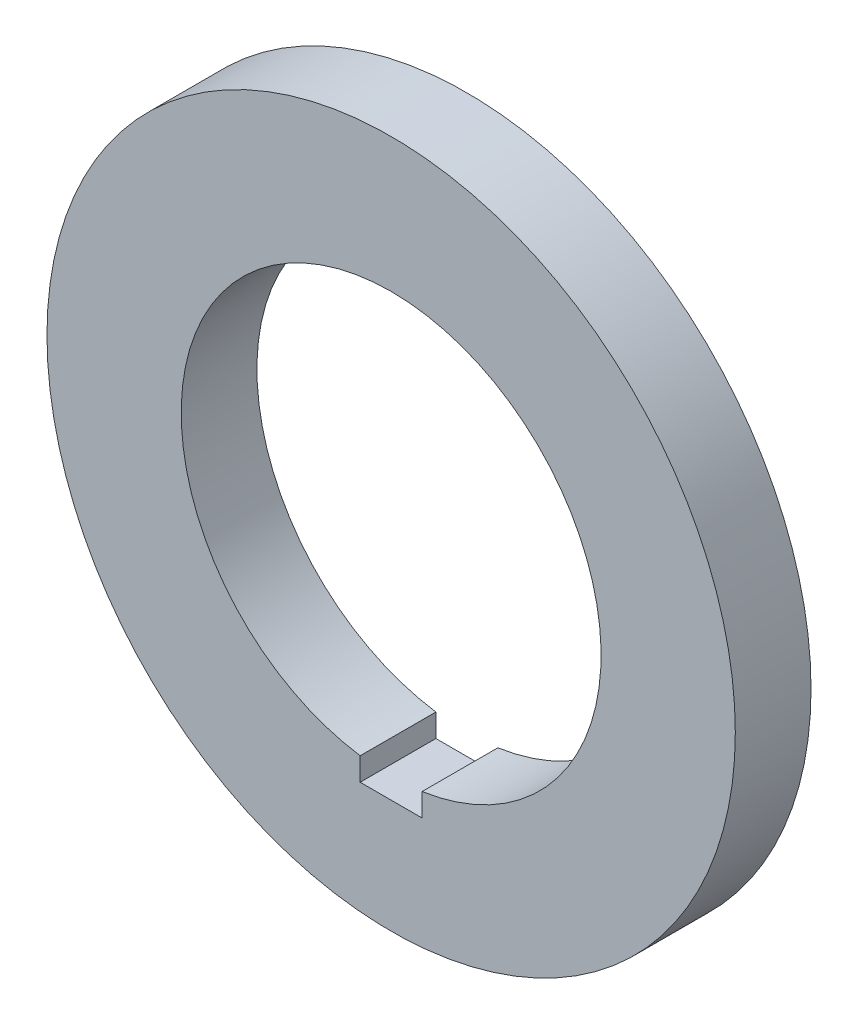
SolidWorks part; units mm, degrees
ref_plane "Front Plane" through (0, 0, 0) normal (0, 0, 1) x (1, 0, 0)
ref_plane "Top Plane" through (0, 0, 0) normal (0, 1, 0) x (1, 0, 0)
ref_plane "Right Plane" through (0, 0, 0) normal (1, 0, 0) x (0, 0, -1)
sketch "Sketch1" plane through (0, 0, 0) normal (0, 0, 1) x (1, 0, 0)
  circle A0 centre (0, 0) radius 25
  circle A1 centre (0, 0) radius 15.25
  dimension "D1" = 50
  dimension "D2" = 30.5
extrude "Boss-Extrude1" add sketch "Sketch1" along normal blind 5.5
sketch "Sketch2" plane through (0, 0, 0) normal (0, 0, -1) x (-1, 0, 0)
  line L1 (-2.25, -16.75) -> (2.25, -16.75)
  line L2 (-2.25, -16.75) -> (-2.25, -13.75)
  line L3 (-2.25, -13.75) -> (2.25, -13.75)
  line L4 (2.25, -16.75) -> (2.25, -13.75)
  line L5 (-2.25, -16.75) -> (2.25, -13.75) construction
  line L6 (-2.25, -13.75) -> (2.25, -16.75) construction
  circle A0 centre (0, 0) radius 15.25 construction
  point P0 (0, -15.25)
  dimension "D1" = 4.5
  dimension "D2" = 3
extrude "Cut-Extrude1" cut sketch "Sketch2" against normal through all
